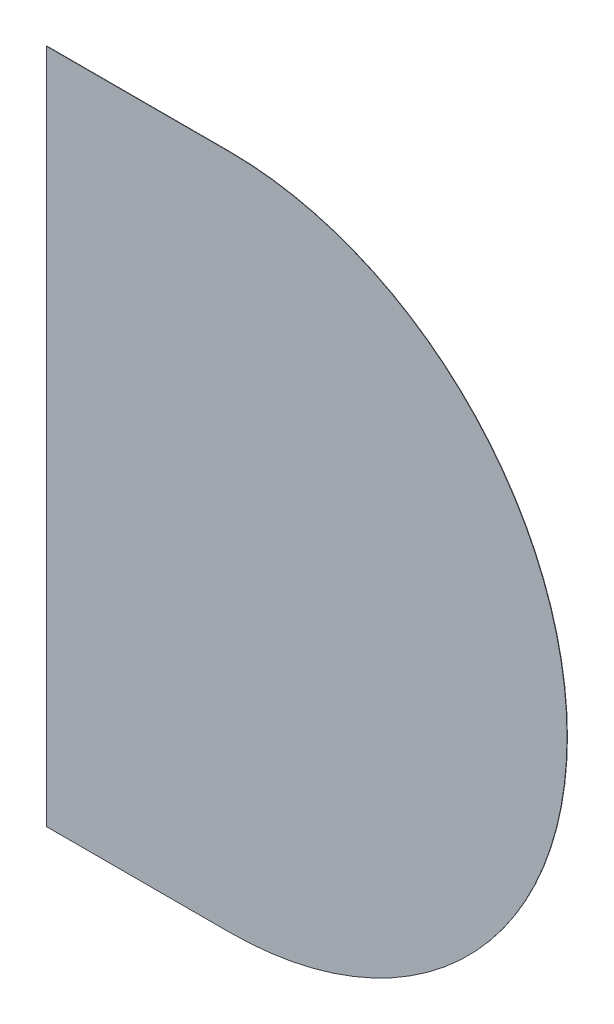
SolidWorks part; units mm, degrees
ref_plane "Front Plane" through (0, 0, 0) normal (0, 0, 1) x (1, 0, 0)
ref_plane "Top Plane" through (0, 0, 0) normal (0, 1, 0) x (1, 0, 0)
ref_plane "Right Plane" through (0, 0, 0) normal (1, 0, 0) x (0, 0, -1)
sketch "Sketch1" plane through (0, 0, 0) normal (0, 0, 1) x (1, 0, 0)
  line L1 (0, 0) -> (470, 0)
  line L2 (0, 0) -> (0, 1740)
  line L3 (0, 1740) -> (470, 1740)
  line L4 (470, 0) -> (470, 1740) construction
  arc A0 (470, 1740) -> (470, 0) centre (470, 870) cw
  dimension "D1" = 470
  dimension "D2" = 1740
extrude "Boss-Extrude1" add sketch "Sketch1" along normal blind 1
